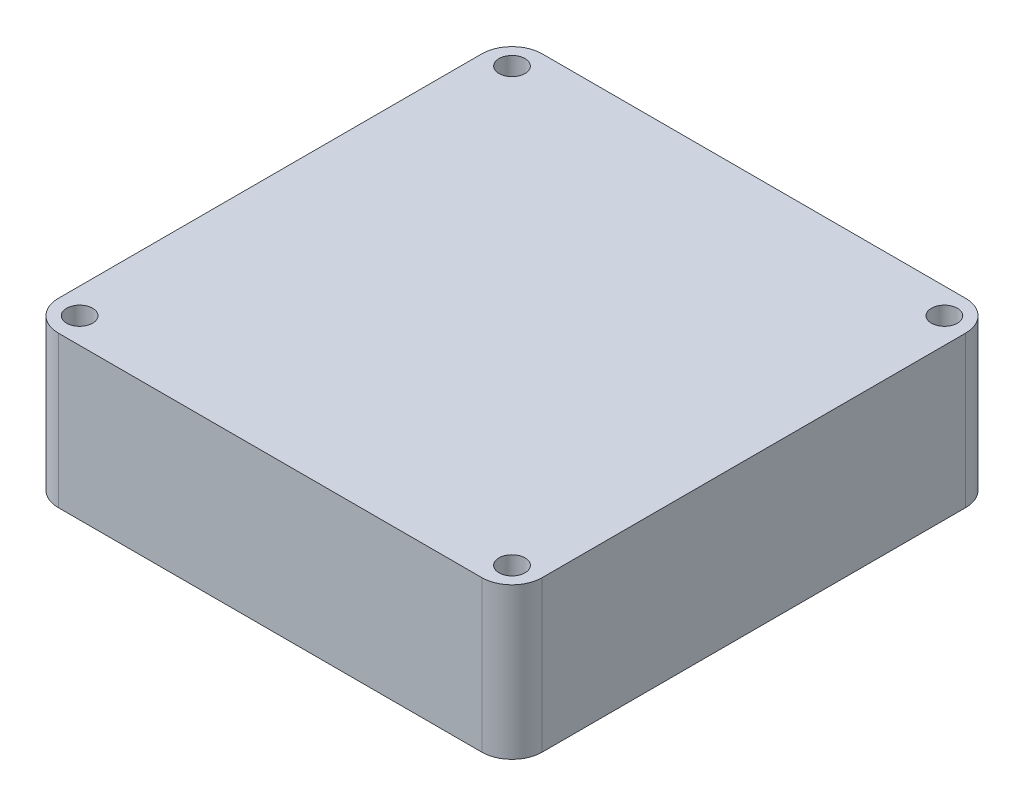
SolidWorks part; units mm, degrees
ref_plane "正面" through (0, 0, 0) normal (0, 0, 1) x (1, 0, 0)
ref_plane "平面" through (0, 0, 0) normal (0, 1, 0) x (1, 0, 0)
ref_plane "右側面" through (0, 0, 0) normal (1, 0, 0) x (0, 0, -1)
sketch "ｽｹｯﾁ1" plane through (0, 0, 0) normal (0, 1, 0) x (1, 0, 0)
  line L1 (-40, 40) -> (40, 40)
  line L2 (-40, 40) -> (-40, -40)
  line L3 (-40, -40) -> (40, -40)
  line L4 (40, 40) -> (40, -40)
  line L5 (-40, 40) -> (40, -40) construction
  line L6 (-40, -40) -> (40, 40) construction
  line L7 (-35.75, 35.75) -> (35.75, 35.75) construction
  line L8 (-35.75, 35.75) -> (-35.75, -35.75) construction
  line L9 (-35.75, -35.75) -> (35.75, -35.75) construction
  line L10 (35.75, 35.75) -> (35.75, -35.75) construction
  line L11 (-35.75, 35.75) -> (35.75, -35.75) construction
  line L12 (-35.75, -35.75) -> (35.75, 35.75) construction
  circle A1 centre (35.75, 35.75) radius 2.15
  circle A2 centre (35.75, -35.75) radius 2.15
  circle A3 centre (-35.75, -35.75) radius 2.15
  circle A4 centre (-35.75, 35.75) radius 2.15
  point P0 (0, 0)
  point P6 (0, 0)
  dimension "D2" = 4.3
  dimension "D1" = 80
  dimension "D3" = 71.5
  dimension "D4" = 4
extrude "ﾎﾞｽ - 押し出し1" add sketch "ｽｹｯﾁ1" along normal blind 25
fillet "ﾌｨﾚｯﾄ1" radius 5 4 edges at (-40, 12.5, -40) (40, 12.5, -40) (40, 12.5, 40) (-40, 12.5, 40)
